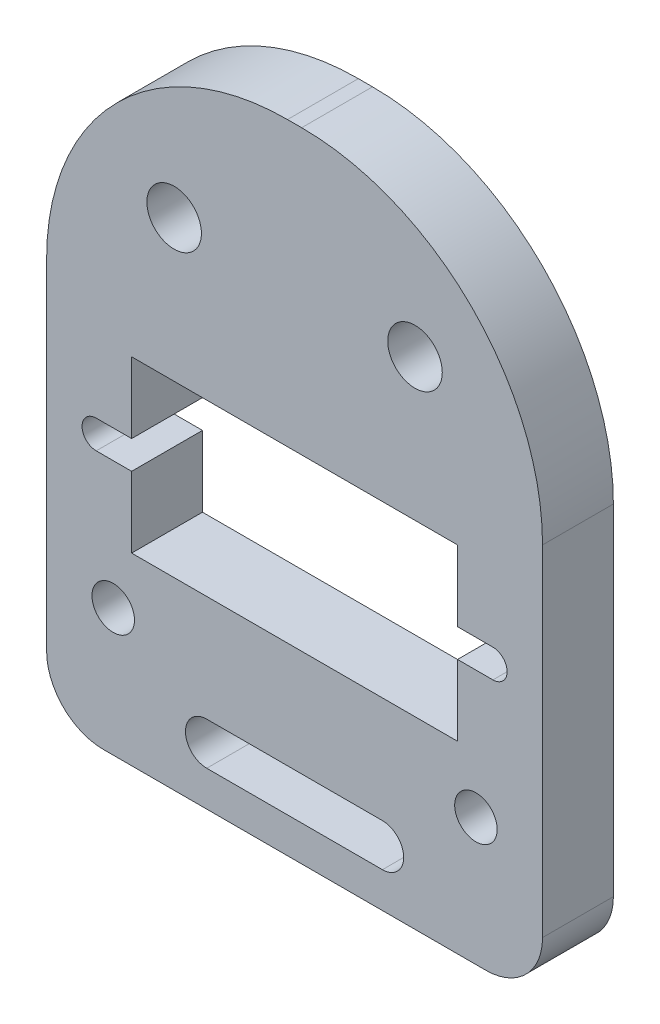
SolidWorks part; units mm, degrees
ref_plane "Plan de face" through (0, 0, 0) normal (0, 0, 1) x (1, 0, 0)
ref_plane "Plan de dessus" through (0, 0, 0) normal (0, 1, 0) x (1, 0, 0)
ref_plane "Plan de droite" through (0, 0, 0) normal (1, 0, 0) x (0, 0, -1)
sketch "Esquisse1" plane through (0, 0, 0) normal (0, 0, 1) x (1, 0, 0)
  line L0 (13.5, -22.5) -> (-13.5, -22.5)
  line L1 (-6.2, -20) -> (6.2, -20)
  line L2 (-17.5, -18.5) -> (-17.5, 5.5)
  line L3 (6.2, -17) -> (-6.2, -17)
  line L4 (-11.5, -9.5) -> (11.5, -9.5)
  line L5 (-14, -4.5) -> (-11.5, -4.5)
  line L6 (11.5, -4.5) -> (14, -4.5)
  line L7 (14, -2.5) -> (11.5, -2.5)
  line L8 (-11.5, -2.5) -> (-14, -2.5)
  line L9 (11.5, 2.5) -> (-11.5, 2.5)
  line L10 (17.5, 5.5) -> (17.5, -18.5)
  line L11 (0, 0) -> (0, -15.8828) construction
  line L12 (-0.5, 22.5) -> (0.5, 22.5)
  line L13 (11.5, -2.5) -> (11.5, 2.5)
  line L14 (11.5, -9.5) -> (11.5, -4.5)
  line L15 (-11.5, -4.5) -> (-11.5, -9.5)
  line L16 (-11.5, 2.5) -> (-11.5, -2.5)
  arc A0 (-7.7, -18.5) -> (-6.2, -20) centre (-6.2, -18.5) ccw
  arc A1 (6.2, -20) -> (7.7, -18.5) centre (6.2, -18.5) ccw
  arc A2 (-6.2, -17) -> (-7.7, -18.5) centre (-6.2, -18.5) ccw
  arc A3 (-0.5, 22.5) -> (-17.5, 5.5) centre (-0.5, 5.5) ccw
  arc A4 (17.5, 5.5) -> (0.5, 22.5) centre (0.5, 5.5) ccw
  arc A5 (-17.5, -18.5) -> (-13.5, -22.5) centre (-13.5, -18.5) ccw
  arc A6 (13.5, -22.5) -> (17.5, -18.5) centre (13.5, -18.5) ccw
  circle A7 centre (8.5, 12.5) radius 1.925
  circle A8 centre (-8.5, 12.5) radius 1.925
  circle A9 centre (-12.8, -13.5) radius 1.5
  circle A10 centre (12.8, -13.5) radius 1.5
  arc A11 (14, -4.5) -> (14, -2.5) centre (14, -3.5) ccw
  arc A12 (-14, -2.5) -> (-14, -4.5) centre (-14, -3.5) ccw
  arc A13 (7.7, -18.5) -> (6.2, -17) centre (6.2, -18.5) ccw
  dimension "D4" = 17
  dimension "D5" = 17
  dimension "D6" = 4
  dimension "D7" = 4
  dimension "D12" = 8.5
  dimension "D1" = 35
  dimension "D2" = 12
  dimension "D3" = 23
  dimension "D8" = 11.5
  dimension "D9" = 14
  dimension "D10" = 14
  dimension "D11" = 8.5
  dimension "D13" = 12.5
  dimension "D14" = 3
  dimension "D15" = 2.5
  dimension "D16" = 12.4
  dimension "D17" = 6.2
  dimension "D18" = 9
  dimension "D19" = 12.8
extrude "Boss.-Extru.1" add sketch "Esquisse1" along normal blind 5
